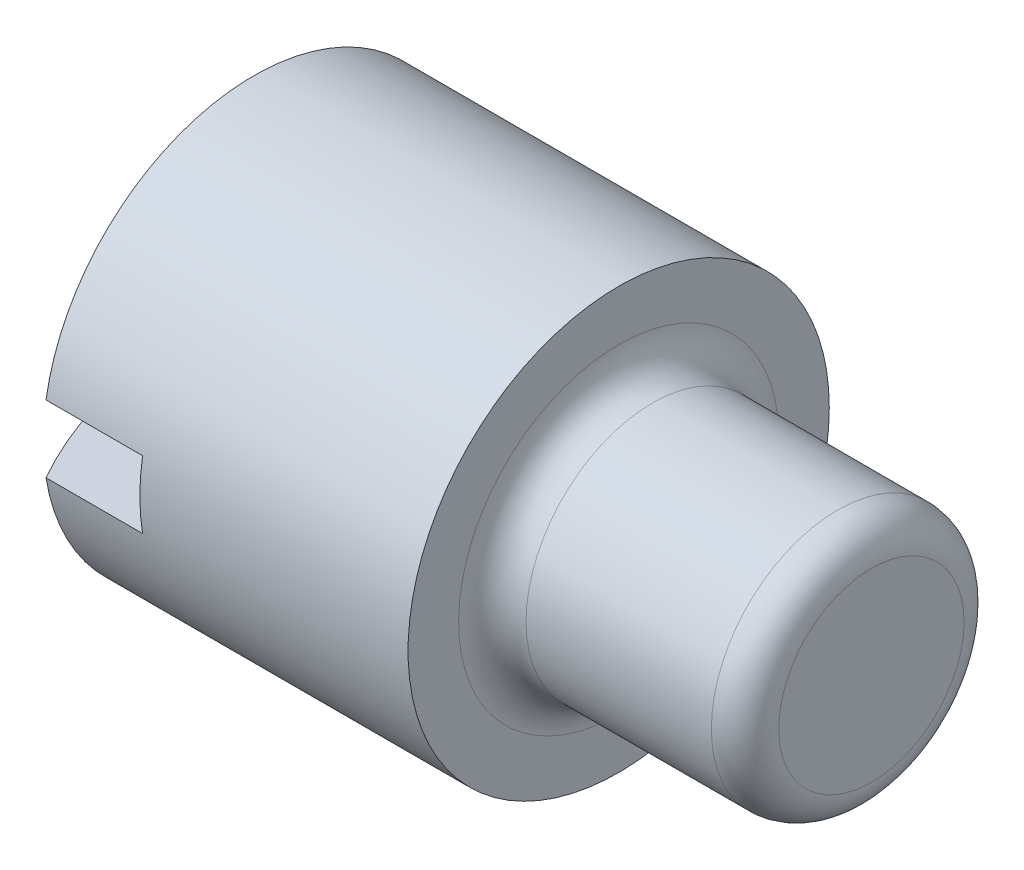
SolidWorks part; units mm, degrees
ref_plane "前视基准面" through (0, 0, 0) normal (0, 0, 1) x (1, 0, 0)
ref_plane "上视基准面" through (0, 0, 0) normal (0, 1, 0) x (1, 0, 0)
ref_plane "右视基准面" through (0, 0, 0) normal (1, 0, 0) x (0, 0, -1)
sketch "草图1" plane through (0, 0, 0) normal (1, 0, 0) x (0, 0, -1)
  line L0 (0, 5) -> (0, -5)
  arc A0 (0, 5) -> (0, -5) centre (0, 0) ccw
  point P4 (0, 0)
  dimension "D1" = 5
revolve "旋转1" add sketch "草图1" angle 180 about L0
sketch "草图2" plane through (0, 0, 0) normal (1, 0, 0) x (0, 0, -1)
  circle A0 centre (0, 0) radius 1.5
  dimension "D1" = 3
extrude "凸台-拉伸1" add sketch "草图2" along normal blind 3
fillet "圆角1" radius 0.4 2 edges at (0, 0, 1.5) (3, 0, -1.5)
sketch "草图3" plane through (0, 0, 0) normal (1, 0, 0) x (0, 0, -1)
  circle A0 centre (0, 0) radius 2.5
  dimension "D1" = 5
extrude "切除-拉伸1" cut sketch "草图3" against normal blind 43 flip side to cut
cosmetic thread "装饰螺纹线1" parameters "D1"=4.3301, "D2"=4.134
sketch "草图4" plane through (0, 0, 0) normal (0, 0, 1) x (1, 0, 0)
  line L0 (0, 0) -> (-3.2391, 0) construction
  line L2 (-5.5935, 0.4) -> (-3.184, 0.4)
  line L3 (-5.5935, 0.4) -> (-5.5935, -0.4)
  line L4 (-5.5935, -0.4) -> (-3.184, -0.4)
  line L5 (-3.184, 0.4) -> (-3.184, -0.4)
  arc A0 (-4.3301, 2.5) -> (-4.3301, -2.5) centre (0, 0) ccw construction
  point P7 (-4.984, -0.4)
  point P8 (0, 0)
  point P12 (0, 0)
  dimension "D1" = 0.8
  dimension "D2" = 1.8
extrude "切除-拉伸2" cut sketch "草图4" against normal mid plane 43
